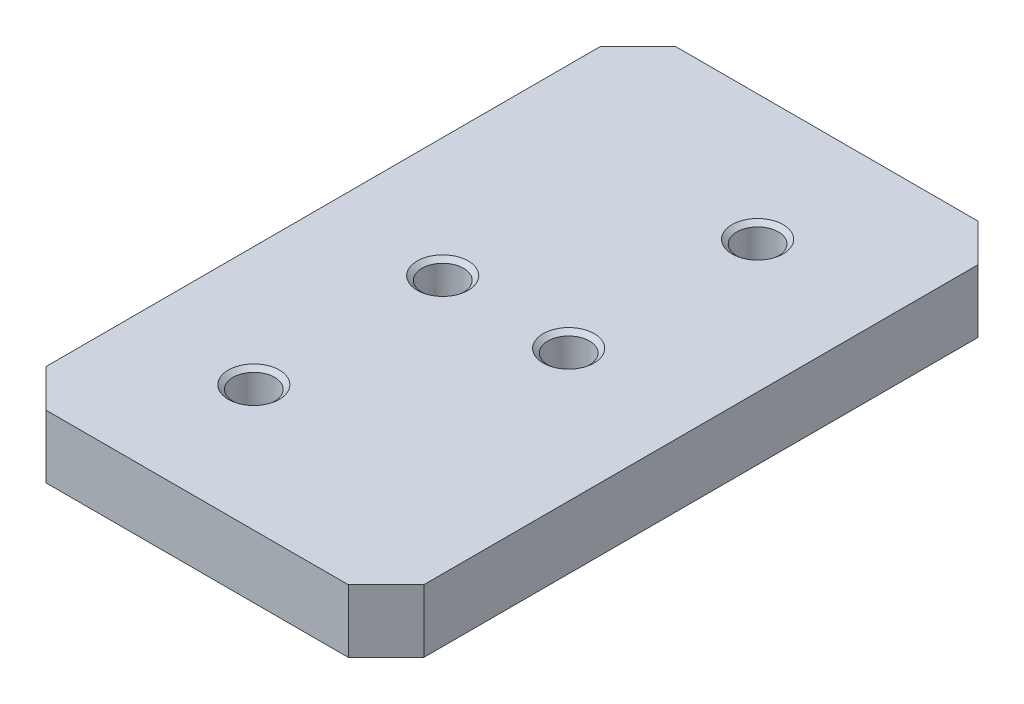
SolidWorks part; units mm, degrees
material "Alloy Steel"
ref_plane "Front Plane" through (0, 0, 0) normal (0, 0, 1) x (1, 0, 0)
ref_plane "Top Plane" through (0, 0, 0) normal (0, 1, 0) x (1, 0, 0)
ref_plane "Right Plane" through (0, 0, 0) normal (1, 0, 0) x (0, 0, -1)
sketch "Sketch1" plane through (0, 0, 0) normal (0, 1, 0) x (1, 0, 0)
  line L1 (-15, -25) -> (15, -25)
  line L2 (-15, -25) -> (-15, 25)
  line L3 (-15, 25) -> (15, 25)
  line L4 (15, -25) -> (15, 25)
  point P0 (0, 0)
  dimension "D1" = 50
  dimension "D2" = 30
extrude "Boss-Extrude1" add sketch "Sketch1" along normal blind 5
hole_wizard "M4x0.7 Tapped Hole1" positions "Sketch2" profile "Sketch3" tap size "M4x0.7" standard "JIS" end condition through all
sketch "Sketch2" plane through (0, 5, 0) normal (0, 1, 0) x (1, 0, 0)
  line L0 (0, 25) -> (0, -25) construction
  line L1 (15, 25) -> (-15, 25) construction
  line L2 (-15, -25) -> (15, -25) construction
  point P0 (-5.5, -15)
  point P2 (-5.5, 0)
  point P4 (4.5, 0)
  point P6 (4.5, 15)
  point P15 (0, 0)
  dimension "D1" = 5.5
  dimension "D2" = 15
  dimension "D3" = 10
  dimension "D4" = 4.5
  dimension "D5" = 15
  dimension "D6" = 10
sketch "Sketch3" plane through (-5.5, 5, 15) normal (1, 0, 0) x (0, 0, 1)
  line L0 (0, 0) -> (0, 5)
  line L1 (0, 5) -> (1.65, 5)
  line L2 (1.65, 5) -> (1.65, 0.3147)
  line L3 (1.65, 0.3147) -> (2.025, 0)
  line L5 (2.025, 0) -> (0, 0)
  line L6 (-1.65, 0.3147) -> (-2.025, 0) construction
  line L11 (0, -6.35) -> (0, 107.95) construction
  dimension "Thru Tap Drill Dia." = 3.3
  dimension "Thru Tap Drill Depth" = 5
  dimension "Near C'Sink Dia." = 4.05
  dimension "Near C'Sink Angle" = 100
cosmetic thread "Hole Thread1"
cosmetic thread "Hole Thread2"
cosmetic thread "Hole Thread3"
cosmetic thread "Hole Thread4"
chamfer "Chamfer1" distance 3 angle 45 4 edges at (-15, 2.5, -25) (-15, 2.5, 25) (15, 2.5, 25) (15, 2.5, -25)
